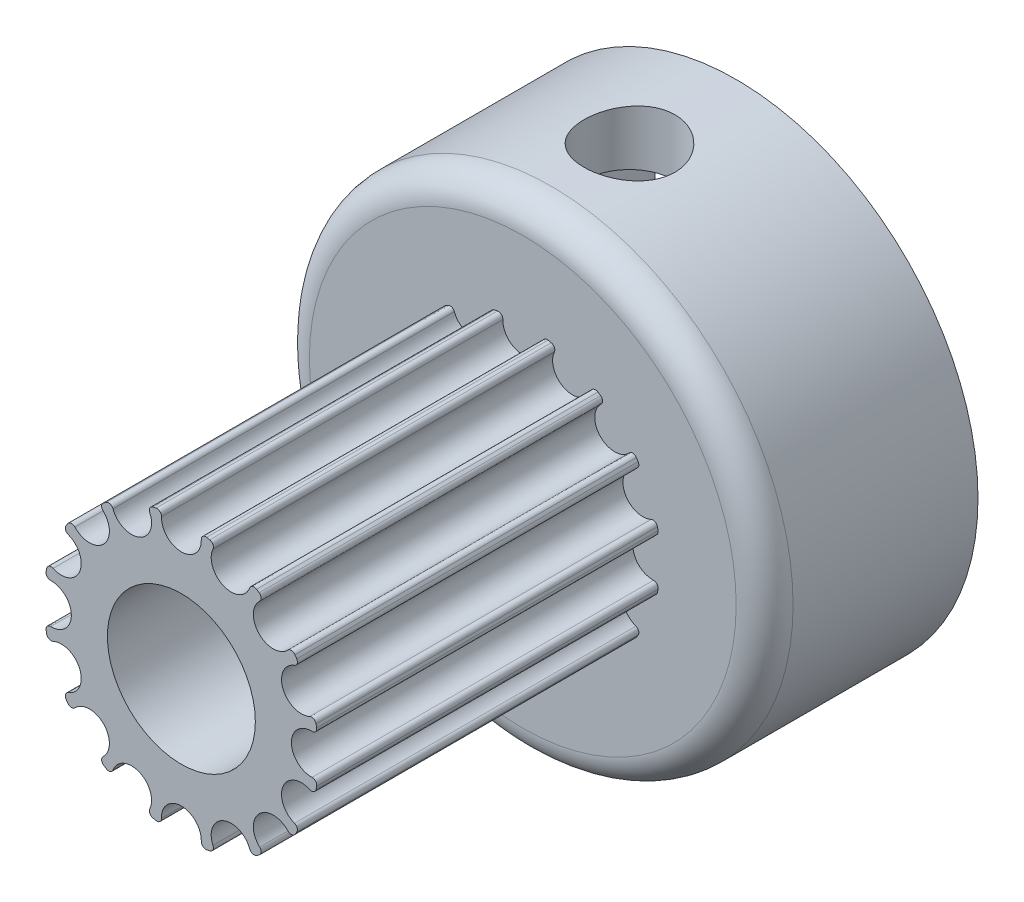
SolidWorks part; units mm, degrees
ref_plane "前视基准面" through (0, 0, 0) normal (0, 0, 1) x (1, 0, 0)
ref_plane "上视基准面" through (0, 0, 0) normal (0, 1, 0) x (1, 0, 0)
ref_plane "右视基准面" through (0, 0, 0) normal (1, 0, 0) x (0, 0, -1)
sketch "草图1" plane through (0, 0, 0) normal (0, 0, 1) x (1, 0, 0)
  circle A0 centre (0, 0) radius 8.5
  circle A1 centre (0, 0) radius 2.6
  dimension "D1" = 17
  dimension "D2" = 5.2
extrude "凸台-拉伸1" add sketch "草图1" along normal blind 7.5
fillet "圆角1" radius 1 1 edges at (8.5, 0, 7.5)
sketch "草图6" plane through (0, 0, 7.5) normal (0, 0, 1) x (1, 0, 0)
  circle A0 centre (0, 0) radius 2.6 construction
  circle A1 centre (0, 0) radius 2.6
  arc B0 (-0.8889, 4.7556) -> (-0.9987, 4.7338) centre (0, 0) ccw
  arc B1 (-0.6996, 4.5927) -> (-0.8889, 4.7556) centre (-0.8595, 4.5983) ccw
  arc B2 (-0.6996, 4.5927) -> (0.6996, 4.5927) centre (0, 4.568) ccw
  arc B3 (0.8889, 4.7556) -> (0.6996, 4.5927) centre (0.8595, 4.5983) ccw
  arc B4 (-2.6411, 4.0535) -> (-2.7342, 3.9912) centre (0, 0) ccw
  arc B5 (-2.4039, 3.9754) -> (-2.6411, 4.0535) centre (-2.5537, 3.9194) ccw
  arc B6 (-2.4039, 3.9754) -> (-1.1112, 4.5108) centre (-1.7481, 4.2202) ccw
  arc B7 (-0.9987, 4.7338) -> (-1.1112, 4.5108) centre (-0.9657, 4.5772) ccw
  arc B8 (-3.9912, 2.7342) -> (-4.0535, 2.6411) centre (0, 0) ccw
  arc B9 (-3.7422, 2.7528) -> (-3.9912, 2.7342) centre (-3.8592, 2.6438) ccw
  arc B10 (-3.7422, 2.7528) -> (-2.7528, 3.7422) centre (-3.23, 3.23) ccw
  arc B11 (-2.7342, 3.9912) -> (-2.7528, 3.7422) centre (-2.6438, 3.8592) ccw
  arc B12 (-4.7338, 0.9987) -> (-4.7556, 0.8889) centre (0, 0) ccw
  arc B13 (-4.5108, 1.1112) -> (-4.7338, 0.9987) centre (-4.5772, 0.9657) ccw
  arc B14 (-4.5108, 1.1112) -> (-3.9754, 2.4039) centre (-4.2202, 1.7481) ccw
  arc B15 (-4.0535, 2.6411) -> (-3.9754, 2.4039) centre (-3.9194, 2.5537) ccw
  arc B16 (-4.7556, -0.8889) -> (-4.7338, -0.9987) centre (0, 0) ccw
  arc B17 (-4.5927, -0.6996) -> (-4.7556, -0.8889) centre (-4.5983, -0.8595) ccw
  arc B18 (-4.5927, -0.6996) -> (-4.5927, 0.6996) centre (-4.568, 0) ccw
  arc B19 (-4.7556, 0.8889) -> (-4.5927, 0.6996) centre (-4.5983, 0.8595) ccw
  arc B20 (-4.0535, -2.6411) -> (-3.9912, -2.7342) centre (0, 0) ccw
  arc B21 (-3.9754, -2.4039) -> (-4.0535, -2.6411) centre (-3.9194, -2.5537) ccw
  arc B22 (-3.9754, -2.4039) -> (-4.5108, -1.1112) centre (-4.2202, -1.7481) ccw
  arc B23 (-4.7338, -0.9987) -> (-4.5108, -1.1112) centre (-4.5772, -0.9657) ccw
  arc B24 (-2.7342, -3.9912) -> (-2.6411, -4.0535) centre (0, 0) ccw
  arc B25 (-2.7528, -3.7422) -> (-2.7342, -3.9912) centre (-2.6438, -3.8592) ccw
  arc B26 (-2.7528, -3.7422) -> (-3.7422, -2.7528) centre (-3.23, -3.23) ccw
  arc B27 (-3.9912, -2.7342) -> (-3.7422, -2.7528) centre (-3.8592, -2.6438) ccw
  arc B28 (-0.9987, -4.7338) -> (-0.8889, -4.7556) centre (0, 0) ccw
  arc B29 (-1.1112, -4.5108) -> (-0.9987, -4.7338) centre (-0.9657, -4.5772) ccw
  arc B30 (-1.1112, -4.5108) -> (-2.4039, -3.9754) centre (-1.7481, -4.2202) ccw
  arc B31 (-2.6411, -4.0535) -> (-2.4039, -3.9754) centre (-2.5537, -3.9194) ccw
  arc B32 (0.8889, -4.7556) -> (0.9987, -4.7338) centre (0, 0) ccw
  arc B33 (0.6996, -4.5927) -> (0.8889, -4.7556) centre (0.8595, -4.5983) ccw
  arc B34 (0.6996, -4.5927) -> (-0.6996, -4.5927) centre (0, -4.568) ccw
  arc B35 (-0.8889, -4.7556) -> (-0.6996, -4.5927) centre (-0.8595, -4.5983) ccw
  arc B36 (2.6411, -4.0535) -> (2.7342, -3.9912) centre (0, 0) ccw
  arc B37 (2.4039, -3.9754) -> (2.6411, -4.0535) centre (2.5537, -3.9194) ccw
  arc B38 (2.4039, -3.9754) -> (1.1112, -4.5108) centre (1.7481, -4.2202) ccw
  arc B39 (0.9987, -4.7338) -> (1.1112, -4.5108) centre (0.9657, -4.5772) ccw
  arc B40 (3.9912, -2.7342) -> (4.0535, -2.6411) centre (0, 0) ccw
  arc B41 (3.7422, -2.7528) -> (3.9912, -2.7342) centre (3.8592, -2.6438) ccw
  arc B42 (3.7422, -2.7528) -> (2.7528, -3.7422) centre (3.23, -3.23) ccw
  arc B43 (2.7342, -3.9912) -> (2.7528, -3.7422) centre (2.6438, -3.8592) ccw
  arc B44 (4.7338, -0.9987) -> (4.7556, -0.8889) centre (0, 0) ccw
  arc B45 (4.5108, -1.1112) -> (4.7338, -0.9987) centre (4.5772, -0.9657) ccw
  arc B46 (4.5108, -1.1112) -> (3.9754, -2.4039) centre (4.2202, -1.7481) ccw
  arc B47 (4.0535, -2.6411) -> (3.9754, -2.4039) centre (3.9194, -2.5537) ccw
  arc B48 (4.7556, 0.8889) -> (4.7338, 0.9987) centre (0, 0) ccw
  arc B49 (4.5927, 0.6996) -> (4.7556, 0.8889) centre (4.5983, 0.8595) ccw
  arc B50 (4.5927, 0.6996) -> (4.5927, -0.6996) centre (4.568, 0) ccw
  arc B51 (4.7556, -0.8889) -> (4.5927, -0.6996) centre (4.5983, -0.8595) ccw
  arc B52 (4.0535, 2.6411) -> (3.9912, 2.7342) centre (0, 0) ccw
  arc B53 (3.9754, 2.4039) -> (4.0535, 2.6411) centre (3.9194, 2.5537) ccw
  arc B54 (3.9754, 2.4039) -> (4.5108, 1.1112) centre (4.2202, 1.7481) ccw
  arc B55 (4.7338, 0.9987) -> (4.5108, 1.1112) centre (4.5772, 0.9657) ccw
  arc B56 (2.7342, 3.9912) -> (2.6411, 4.0535) centre (0, 0) ccw
  arc B57 (2.7528, 3.7422) -> (2.7342, 3.9912) centre (2.6438, 3.8592) ccw
  arc B58 (2.7528, 3.7422) -> (3.7422, 2.7528) centre (3.23, 3.23) ccw
  arc B59 (3.9912, 2.7342) -> (3.7422, 2.7528) centre (3.8592, 2.6438) ccw
  arc B60 (0.9987, 4.7338) -> (0.8889, 4.7556) centre (0, 0) ccw
  arc B61 (1.1112, 4.5108) -> (0.9987, 4.7338) centre (0.9657, 4.5772) ccw
  arc B62 (1.1112, 4.5108) -> (2.4039, 3.9754) centre (1.7481, 4.2202) ccw
  arc B63 (2.6411, 4.0535) -> (2.4039, 3.9754) centre (2.5537, 3.9194) ccw
sketch_block_instance "块1-1"
sketch_block "块1"
extrude "凸台-拉伸2" add sketch "草图6" along normal blind 12
sketch "草图4" plane through (0, 0, 0) normal (0, 1, 0) x (1, 0, 0)
  line L0 (8.5, 0) -> (-8.5, 0) construction
  circle A0 centre (0, -3.75) radius 1.6
  dimension "D1" = 3.2
  dimension "D2" = 3.75
extrude "切除-拉伸1" cut sketch "草图4" against normal through all and the other way through all
sketch "草图5" plane through (0, 0, 0) normal (0, 0, -1) x (-1, 0, 0)
  line L0 (0, 0) -> (0, 9.103) construction
  line L1 (-2.85, 6.5) -> (2.85, 6.5)
  line L2 (-2.85, 6.5) -> (-2.85, 3.8)
  line L3 (-2.85, 3.8) -> (2.85, 3.8)
  line L4 (2.85, 6.5) -> (2.85, 3.8)
  dimension "D1" = 3.8
  dimension "D2" = 2.7
  dimension "D3" = 5.7
extrude "切除-拉伸2" cut sketch "草图5" against normal blind 7.05
mirror "镜向1" about plane through (0, 0, 0) normal (0, 1, 0) of "切除-拉伸2", "切除-拉伸1"
